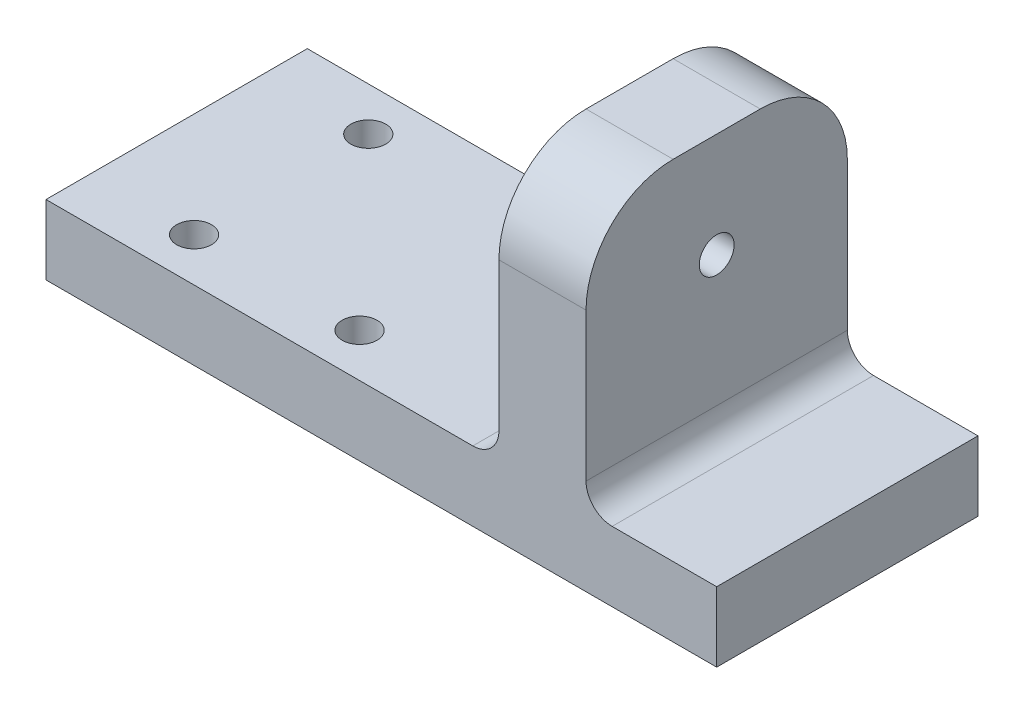
SolidWorks part; units mm, degrees
ref_plane "Front Plane" through (0, 0, 0) normal (0, 0, 1) x (1, 0, 0)
ref_plane "Top Plane" through (0, 0, 0) normal (0, 1, 0) x (1, 0, 0)
ref_plane "Right Plane" through (0, 0, 0) normal (1, 0, 0) x (0, 0, -1)
sketch "Sketch1" plane through (0, 0, 0) normal (0, 1, 0) x (1, 0, 0)
  line L1 (-20, 15) -> (20, 15)
  line L2 (-20, 15) -> (-20, -15)
  line L3 (-20, -15) -> (20, -15)
  line L4 (20, 15) -> (20, -15)
  line L5 (-20, 15) -> (20, -15) construction
  line L6 (-20, -15) -> (20, 15) construction
  point P0 (0, 0)
  dimension "D1" = 40
  dimension "D2" = 30
extrude "Boss-Extrude1" add sketch "Sketch1" along normal blind 8
sketch "Sketch2" plane through (0, 8, 0) normal (0, 1, 0) x (1, 0, 0)
  line L0 (-20, -15) -> (20, -15) construction
  line L1 (-5, 15) -> (5, 15)
  line L2 (-5, 15) -> (-5, -15)
  line L3 (-5, -15) -> (5, -15)
  line L4 (5, 15) -> (5, -15)
  line L5 (-5, 15) -> (5, -15) construction
  line L6 (-5, -15) -> (5, 15) construction
  point P0 (0, 0)
  dimension "D1" = 10
extrude "Boss-Extrude2" add sketch "Sketch2" along normal blind 30
fillet "Fillet2" radius 3 2 edges at (-5, 8, 0) (5, 8, 0)
sketch "Sketch4" plane through (5, 0, 0) normal (1, 0, 0) x (0, 0, -1)
  line L0 (0, 38) -> (0, 26) construction
  line L1 (-15, 38) -> (15, 38) construction
  circle A0 centre (0, 26) radius 2
  dimension "D2" = 4
  dimension "D1" = 12
extrude "Cut-Extrude2" cut sketch "Sketch4" against normal blind 10
fillet "Fillet3" radius 10 2 edges at (0, 38, 15) (0, 38, -15)
sketch "Sketch5" plane through (-20, 0, 0) normal (-1, 0, 0) x (0, 0, 1)
  line L1 (-15, 8) -> (15, 8)
  line L2 (-15, 8) -> (-15, 0)
  line L3 (-15, 0) -> (15, 0)
  line L4 (15, 8) -> (15, 0)
extrude "Boss-Extrude3" add sketch "Sketch5" along normal blind 37
sketch "Sketch8" plane through (0, 8, 0) normal (0, 1, 0) x (1, 0, 0)
  line L0 (-45, 15) -> (-45, -15) construction
  line L1 (-8, 15) -> (-57, 15) construction
  line L2 (-57, -15) -> (-8, -15) construction
  line L3 (-57, -15) -> (-57, 15) construction
  line L4 (-26, 15) -> (-26, -15) construction
  line L5 (-45, 15) -> (-26, 15) construction
  line L6 (-35.5, 15) -> (-35.5, 0) construction
  line L7 (-35.5, 0) -> (-57, 0) construction
  line L8 (-8, 15) -> (-57, 15) construction
  circle A0 centre (-45, 10) radius 2
  circle A1 centre (-45, -10) radius 2
  circle A2 centre (-26, -10) radius 2
  circle A3 centre (-26, 10) radius 2
  dimension "D2" = 5
  dimension "D1" = 31
  dimension "0.65" = 12
extrude "Cut-Extrude3" cut sketch "Sketch8" against normal blind 37
